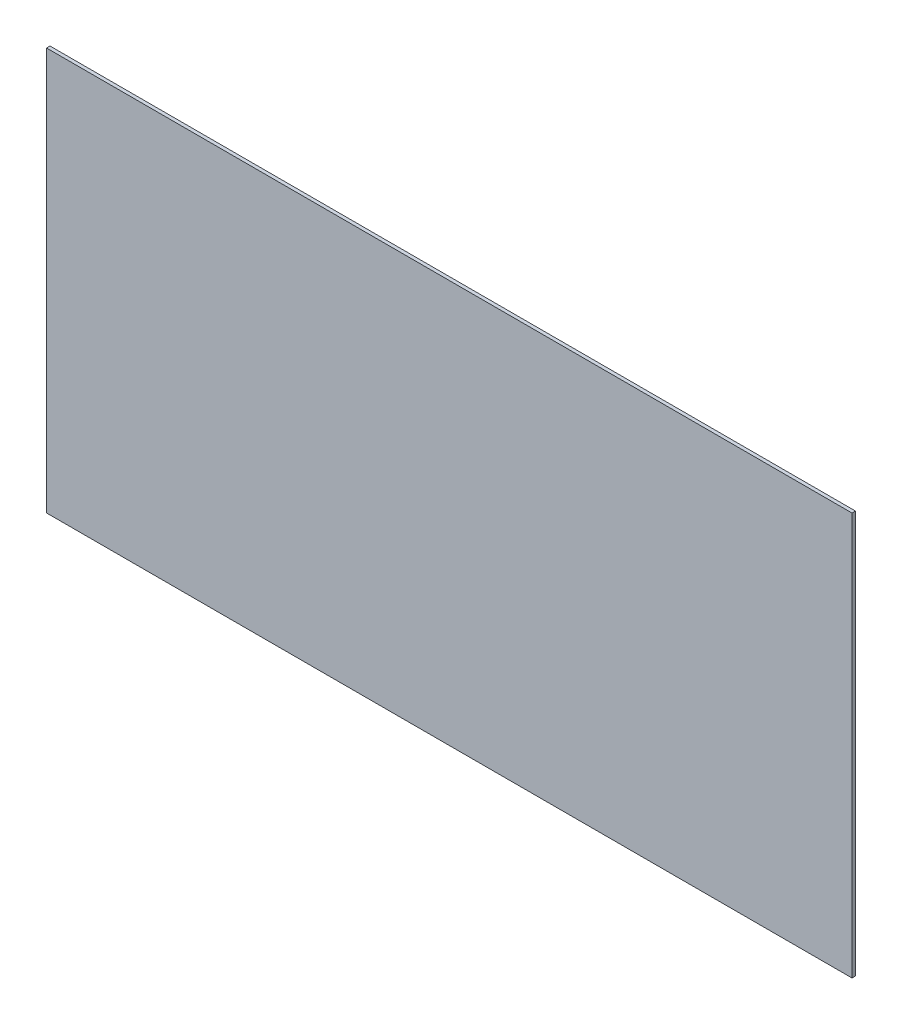
SolidWorks part; units mm, degrees
ref_plane "Ön Düzlem" through (0, 0, 0) normal (0, 0, 1) x (1, 0, 0)
ref_plane "Üst Düzlem" through (0, 0, 0) normal (0, 1, 0) x (1, 0, 0)
ref_plane "Sağ Düzlem" through (0, 0, 0) normal (1, 0, 0) x (0, 0, -1)
sketch "Çizim1" plane through (0, 0, 0) normal (0, 0, 1) x (1, 0, 0)
  line L1 (-263.9344, 175) -> (436.0656, 175)
  line L2 (-263.9344, 175) -> (-263.9344, -175)
  line L3 (-263.9344, -175) -> (436.0656, -175)
  line L4 (436.0656, 175) -> (436.0656, -175)
  dimension "D1" = 700
  dimension "D2" = 350
extrude "Yükseklik-Ekstrüzyon1" add sketch "Çizim1" along normal blind 3
